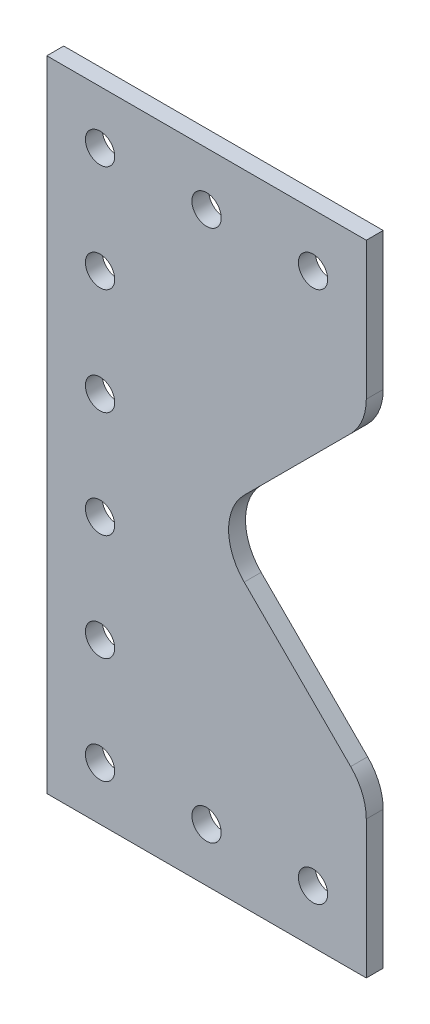
SolidWorks part; units mm, degrees
ref_plane "Front Plane" through (0, 0, 0) normal (0, 0, 1) x (1, 0, 0)
ref_plane "Top Plane" through (0, 0, 0) normal (0, 1, 0) x (1, 0, 0)
ref_plane "Right Plane" through (0, 0, 0) normal (1, 0, 0) x (0, 0, -1)
sketch "Sketch1" plane through (0, 0, 0) normal (0, 0, 1) x (1, 0, 0)
  line L0 (0, 0) -> (0, 120)
  line L1 (0, 60) -> (30, 60) construction
  line L2 (30, 60) -> (60, 30)
  line L3 (60, 30) -> (60, 0)
  line L4 (60, 0) -> (0, 0)
  line L5 (60, 120) -> (0, 120)
  line L6 (60, 90) -> (60, 120)
  line L7 (30, 60) -> (60, 90)
  dimension "D1" = 30
  dimension "D2" = 120
  dimension "D3" = 60
extrude "Boss-Extrude1" add sketch "Sketch1" along normal blind 3.175
hole_wizard "M5 Clearance Hole1" positions "3DSketch1" profile "Sketch2" hole size "M5" standard "ANSI Metric" end condition through all
sketch3d "3DSketch1"
  line L0 (0, 120, 3.175) -> (0, 0, 3.175) construction
  line L1 (0, 0, 3.175) -> (60, 0, 3.175) construction
  point P4 (10, 10, 3.175)
  dimension "D1" = 10
  dimension "D2" = 10
sketch "Sketch2" plane through (10, 10, 3.175) normal (1, 0, 0) x (0, -1, 0)
  line L0 (0, 0) -> (0, 3.175)
  line L1 (0, 3.175) -> (2.75, 3.175)
  line L2 (2.75, 3.175) -> (2.75, 0)
  line L5 (2.75, 0) -> (0, 0)
  line L11 (0, -6.35) -> (0, 107.95) construction
  dimension "Thru Hole Dia." = 5.5
  dimension "Thru Hole Depth" = 3.175
pattern_linear "LPattern1" count 3 spacing 20 along (1, 0, 0) of "M5 Clearance Hole1"
pattern_linear "LPattern2" count 6 spacing 20 along (0, 1, 0) of "M5 Clearance Hole1"
fillet "Fillet2" radius 10 3 edges at (60, 30, 1.5875) (60, 90, 1.5875) (30, 60, 1.5875)
pattern_linear "LPattern3" count 2 spacing 100 along (0, 1, 0) of "LPattern1"
